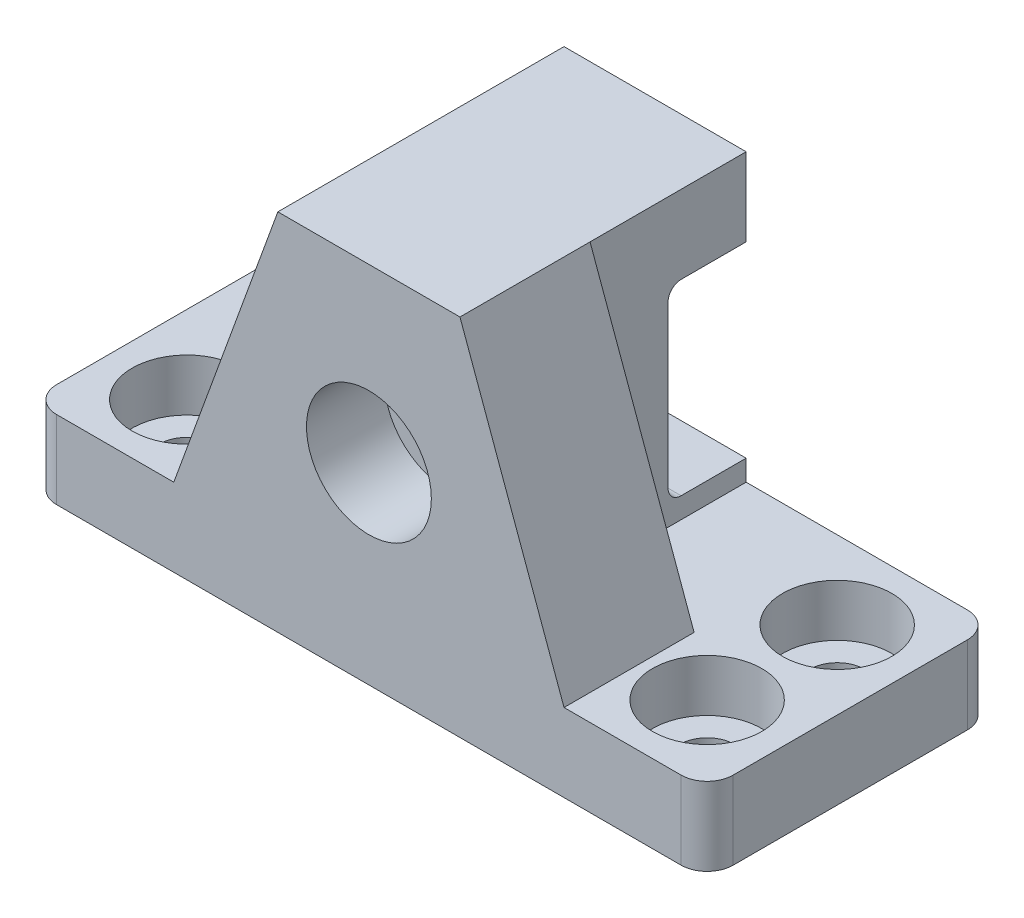
SolidWorks part; units mm, degrees
ref_plane "Front Plane" through (0, 0, 0) normal (0, 0, 1) x (1, 0, 0)
ref_plane "Top Plane" through (0, 0, 0) normal (0, 1, 0) x (1, 0, 0)
ref_plane "Right Plane" through (0, 0, 0) normal (1, 0, 0) x (0, 0, -1)
sketch "Sketch1" plane through (0, 0, 0) normal (0, 1, 0) x (1, 0, 0)
  line L1 (-13, -5.5) -> (13, -5.5)
  line L2 (-13, -5.5) -> (-13, 5.5)
  line L3 (-13, 5.5) -> (13, 5.5)
  line L4 (13, -5.5) -> (13, 5.5)
  line L5 (-13, -5.5) -> (13, 5.5) construction
  line L6 (-13, 5.5) -> (13, -5.5) construction
  line L7 (-10, -2.5) -> (10, -2.5) construction
  line L8 (-10, -2.5) -> (-10, 2.5) construction
  line L9 (-10, 2.5) -> (10, 2.5) construction
  line L10 (10, -2.5) -> (10, 2.5) construction
  line L11 (-10, -2.5) -> (10, 2.5) construction
  line L12 (-10, 2.5) -> (10, -2.5) construction
  circle A0 centre (-10, 2.5) radius 1.05
  circle A1 centre (-10, -2.5) radius 1.05
  circle A2 centre (10, 2.5) radius 1.05
  circle A3 centre (10, -2.5) radius 1.05
  point P0 (0, 0)
  point P6 (0, 0)
  dimension "D3" = 5
  dimension "D5" = 2.1
  dimension "D1" = 26
  dimension "D2" = 11
  dimension "D4" = 20
extrude "Boss-Extrude1" add sketch "Sketch1" along normal blind 3
sketch "Sketch10" plane through (0, 3, 0) normal (0, 1, 0) x (1, 0, 0)
  circle A0 centre (-10, 2.5) radius 2.1
  circle A1 centre (-10, -2.5) radius 2.1
  circle A2 centre (10, 2.5) radius 2.1
  circle A3 centre (10, -2.5) radius 2.1
  dimension "D1" = 4.2
extrude "Cut-Extrude6" cut sketch "Sketch10" against normal blind 2
sketch "Sketch3" plane through (0, 0, -5.5) normal (0, 0, -1) x (-1, 0, 0)
  line L0 (-13, 0) -> (13, 0) construction
  line L1 (-3.5, 0) -> (3.5, 0)
  line L2 (-3.5, 0) -> (-3.5, 14)
  line L3 (-3.5, 14) -> (3.5, 14)
  line L4 (3.5, 0) -> (3.5, 14)
  line L5 (0, 14) -> (0, 0) construction
  dimension "D1" = 14
  dimension "D2" = 7
extrude "Boss-Extrude2" add sketch "Sketch3" against normal up to surface (11 mm away) up to face at (0, 1.5, 5.5)
sketch "Sketch6" plane through (3.5, 0, 0) normal (1, 0, 0) x (0, 0, -1)
  line L0 (5.5, 14) -> (5.5, 3) construction
  line L1 (5.5, 11) -> (2.5, 11)
  line L2 (5.5, 11) -> (5.5, 3.8)
  line L3 (5.5, 3.8) -> (2.5, 3.8)
  line L4 (2.5, 11) -> (2.5, 3.8)
  line L6 (2.5, 7.4) -> (5.5, 7.4) construction
  line L7 (-5.5, 0) -> (5.5, 0) construction
  dimension "D1" = 11
  dimension "D2" = 7.2
  dimension "D3" = 3
extrude "Cut-Extrude3" cut sketch "Sketch6" against normal through all
sketch "Sketch7" plane through (0, 0, -2.5) normal (0, 0, -1) x (-1, 0, 0)
  line L0 (-3.5, 11) -> (3.5, 3.8) construction
  circle A0 centre (0, 7.4) radius 1.35
  dimension "D1" = 2.7
extrude "Cut-Extrude4" cut sketch "Sketch7" against normal through all
sketch "Sketch8" plane through (0, 0, 5.5) normal (0, 0, 1) x (1, 0, 0)
  circle A0 centre (0, 7.4) radius 2.4
  dimension "D1" = 4.8
extrude "Cut-Extrude5" cut sketch "Sketch8" against normal offset from surface (3 mm away) 5 up to face at (0, 8.75, -2.5)
fillet "Fillet1" radius 0.5 2 edges at (0, 3.8, -2.5) (0, 11, -2.5)
fillet "Fillet2" radius 1 4 edges at (-13, 1.5, -5.5) (-13, 1.5, 5.5) (13, 1.5, -5.5) (13, 1.5, 5.5)
sketch "Sketch9" plane through (0, 0, 5.5) normal (0, 0, 1) x (1, 0, 0)
  line L0 (3.5, 3) -> (3.5, 14)
  line L1 (3.5, 3) -> (3.5, 14) construction
  line L2 (3.5, 14) -> (7.5, 3)
  line L3 (3.5, 3) -> (12, 3) construction
  line L4 (7.5, 3) -> (3.5, 3)
  line L5 (0, 14) -> (0, 0) construction
  line L6 (3.5, 14) -> (-3.5, 14) construction
  line L7 (-7.5, 3) -> (-3.5, 3)
  line L8 (-3.5, 14) -> (-7.5, 3)
  line L9 (-3.5, 3) -> (-3.5, 14)
  point P16 (3.5, 14)
  dimension "D1" = 4
extrude "Boss-Extrude3" add sketch "Sketch9" against normal blind 5
